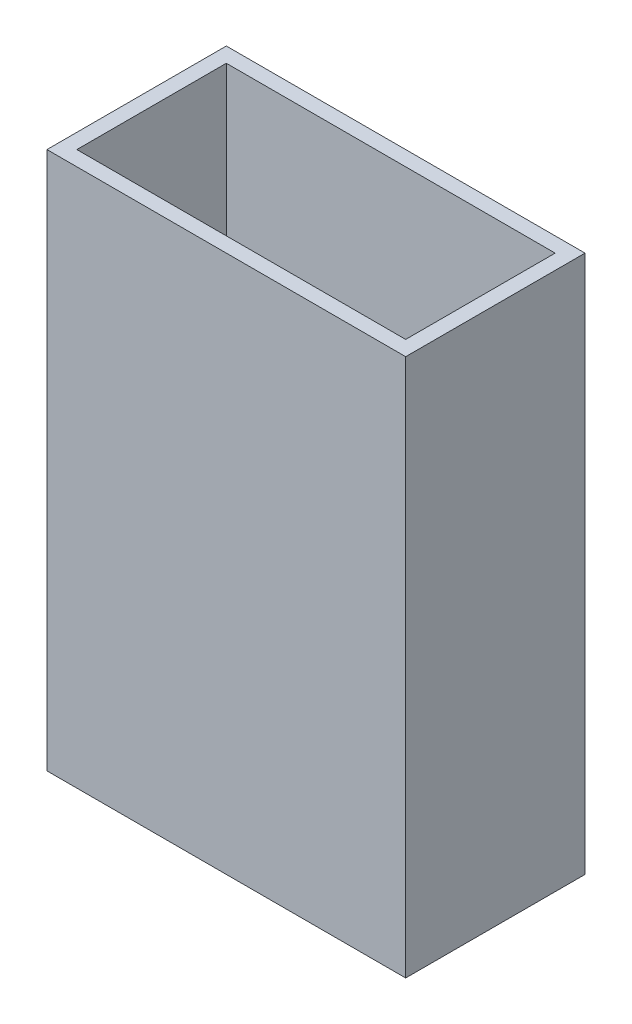
SolidWorks part; units mm, degrees
ref_plane "Front Plane" through (0, 0, 0) normal (0, 0, 1) x (1, 0, 0)
ref_plane "Top Plane" through (0, 0, 0) normal (0, 1, 0) x (1, 0, 0)
ref_plane "Right Plane" through (0, 0, 0) normal (1, 0, 0) x (0, 0, -1)
sketch "Sketch1" plane through (0, 0, 0) normal (0, 0, 1) x (1, 0, 0)
  line L1 (0, 0) -> (152.4, 0)
  line L2 (0, 0) -> (0, 228.6)
  line L3 (0, 228.6) -> (152.4, 228.6)
  line L4 (152.4, 0) -> (152.4, 228.6)
  dimension "D1" = 152.4
  dimension "D2" = 228.6
extrude "Boss-Extrude1" add sketch "Sketch1" along normal blind 76.2
shell "Shell1" thickness 6.35
